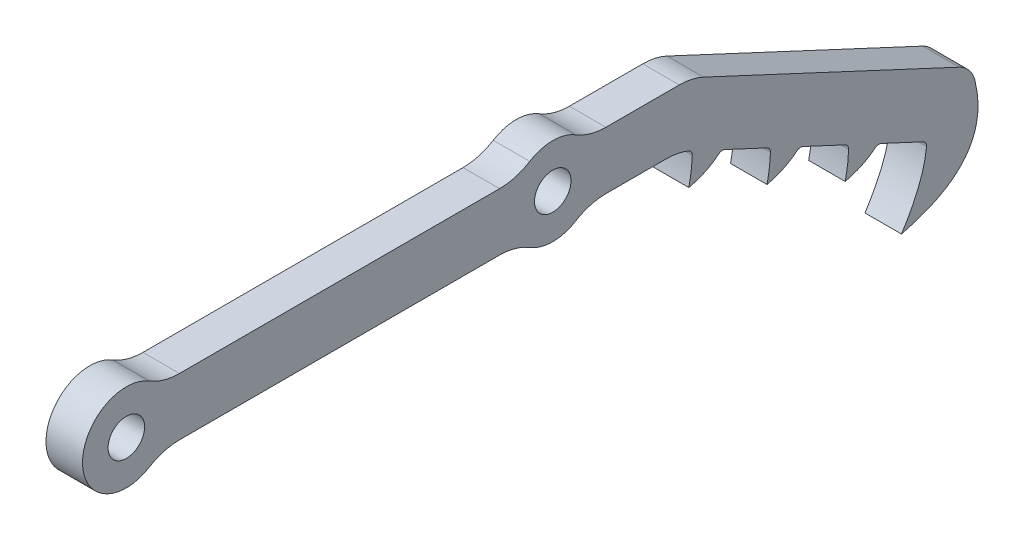
SolidWorks part; units mm, degrees
material "6061 Alloy"
ref_plane "Front Plane" through (0, 0, 0) normal (0, 0, 1) x (1, 0, 0)
ref_plane "Top Plane" through (0, 0, 0) normal (0, 1, 0) x (1, 0, 0)
ref_plane "Right Plane" through (0, 0, 0) normal (1, 0, 0) x (0, 0, -1)
sketch "Sketch1" plane through (0, 0, 0) normal (1, 0, 0) x (0, 0, -1)
  line L0 (-57.9219, 44.5435) -> (-40.0493, 54.8622)
  line L1 (-40.0493, 49.8622) -> (56.1047, 49.8622)
  line L2 (56.1047, 49.8622) -> (102.5472, 28.2057)
  line L3 (-40.0493, 59.8622) -> (58.3217, 59.8622)
  line L4 (58.3217, 59.8622) -> (106.7734, 37.2688)
  line L5 (56.1047, 49.8622) -> (84.5622, 36.5923) construction
  line L6 (58.3217, 59.8622) -> (88.7883, 45.6554) construction
  line L7 (102.5472, 28.2057) -> (106.7734, 37.2688)
  line L8 (102.5472, 28.2057) -> (111.6103, 23.9795)
  line L9 (93.4842, 32.4319) -> (106.7734, 37.2688)
  line L10 (56.1047, 49.8622) -> (58.3217, 59.8622) construction
  circle A0 centre (-57.9219, 44.5435) radius 15.875
  circle A1 centre (-40.0493, 54.8622) radius 4.7625
  circle A2 centre (-40.0493, 54.8622) radius 2.5
  circle A3 centre (-40.0493, 54.8622) radius 5
  circle A4 centre (-40.0493, 54.8622) radius 7.62
  circle A6 centre (34.1047, 54.8622) radius 7.62
  parabola Q0 (106.7734, 37.2688) -> (94.7552, 18.0752) focus (102.5472, 28.2057) apex (107.0788, 26.0926)
  parabola Q1 (99.1632, 29.7837) -> (94.7552, 18.0752) focus (93.4842, 32.4319) apex (98.5101, 34.2612)
  parabola Q2 (93.4202, 43.4955) -> (84.9631, 30.8885) focus (87.9414, 37.2725) apex (91.341, 34.5621)
  parabola Q3 (85.5686, 36.123) -> (84.9631, 30.8885) focus (78.3442, 40.2408) apex (83.762, 43.3694)
  parabola Q4 (79.8256, 49.8348) -> (71.3685, 37.2277) focus (74.3468, 43.6117) apex (77.7464, 40.9013)
  parabola Q5 (71.974, 42.4623) -> (71.3685, 37.2277) focus (64.7496, 46.58) apex (70.1674, 49.7086)
  parabola Q6 (66.2309, 56.1741) -> (57.7739, 43.567) focus (60.7522, 49.951) apex (64.1518, 47.2406)
  parabola Q7 (58.3794, 48.8015) -> (57.7739, 43.567) focus (51.155, 52.9193) apex (56.5728, 56.0479)
  point P12 (93.4842, 32.4319)
  point P19 (100.1288, 34.8504)
  point P46 (57.2132, 54.8622)
  point P47 (34.1047, 54.8622)
  dimension "D1" = 10
  dimension "D5" = 10
  dimension "D2" = 12.4745
  dimension "D3" = 5
  dimension "D4" = 15
  dimension "D6" = 5
  dimension "D7" = 22
extrude "Boss-Extrude1" add sketch "Sketch1" along normal blind 6.35
sketch "Sketch7" plane through (6.35, 0, 0) normal (1, 0, 0) x (0, 0, -1)
  point P0 (-40.0493, 54.8622)
  point P1 (34.1047, 54.8622)
hole_wizard "1/4 (0.2500) Dowel Hole4" positions "Sketch7" profile "Sketch8" hole size "1/4" standard "ANSI Inch" end condition through all
sketch "Sketch8" plane through (6.35, 54.8622, 40.0493) normal (0, 1, 0) x (0, 0, -1)
  line L0 (0, 0) -> (0, 6.35)
  line L1 (0, 6.35) -> (3.175, 6.35)
  line L2 (3.175, 6.35) -> (3.175, 0)
  line L5 (3.175, 0) -> (0, 0)
  line L11 (0, -6.35) -> (0, 107.95) construction
  dimension "Thru Hole Dia." = 6.35
  dimension "Thru Hole Depth" = 6.35
fillet "Fillet1" radius 10 2 edges at (3.175, 59.8622, 34.2992) (3.175, 49.8622, 34.2992)
fillet "Fillet2" radius 10 2 edges at (3.175, 49.8622, -56.1047) (3.175, 59.8622, -58.3217)
fillet "Fillet4" radius 5 1 edges at (3.175, 37.2688, -106.7734)
fillet "Fillet5" radius 1 7 edges at (3.175, 33.7664, -90.6224) (3.175, 40.1057, -77.0278) (3.175, 46.4449, -63.4331) (3.175, 48.8015, -58.3794) (3.175, 42.4623, -71.974) (3.175, 36.123, -85.5686) (3.175, 29.7837, -99.1632)
fillet "Fillet6" radius 10 4 edges at (3.175, 49.8622, -39.8549) (3.175, 49.8622, -28.3545) (3.175, 59.8622, -28.3545) (3.175, 59.8622, -39.8549)
